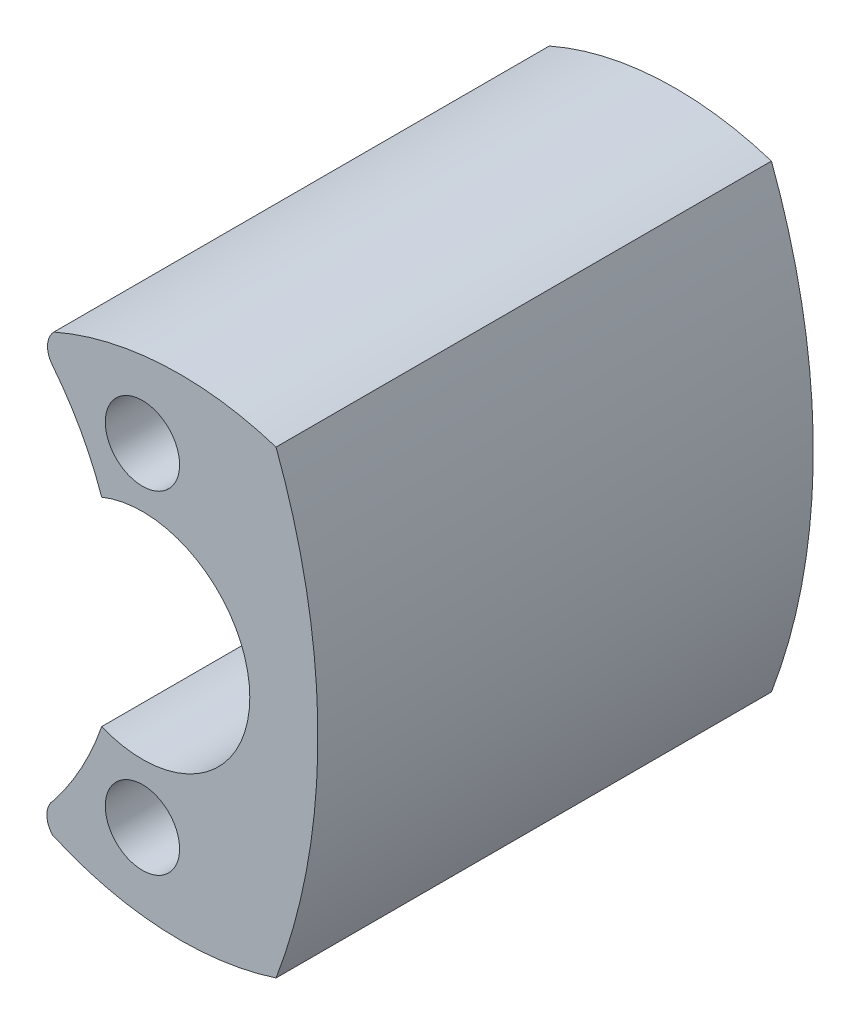
SolidWorks part; units mm, degrees
ref_plane "Front Plane" through (0, 0, 0) normal (0, 0, 1) x (1, 0, 0)
ref_plane "Top Plane" through (0, 0, 0) normal (0, 1, 0) x (1, 0, 0)
ref_plane "Right Plane" through (0, 0, 0) normal (1, 0, 0) x (0, 0, -1)
sketch "Sketch1" plane through (0, 0, 0) normal (0, 0, 1) x (1, 0, 0)
  line L0 (0, 0) -> (0, 9.5) construction
  arc A0 (5.3943, 9.2817) -> (5.3943, -9.2817) centre (-19.2657, 0) cw
  arc A1 (-3.6387, 7.6355) -> (-3.5758, 8.8197) centre (-2.9394, 8.1921) cw
  arc A2 (-3.5758, 8.8197) -> (5.3943, 9.2817) centre (1.5165, -2.7402) cw
  arc A3 (-3.6387, 7.6355) -> (-3.5758, -7.5558) centre (-13.2313, 0) cw
  arc A5 (-3.5758, -7.5558) -> (-3.6256, -8.7977) centre (-2.9797, -8.2016) ccw
  arc A7 (-3.6256, -8.7977) -> (5.3943, -9.2817) centre (1.5165, 2.7402) ccw
  point P12 (0, 0)
  point P13 (5.3943, -9.4493)
  point P18 (5.2209, 9.2817)
extrude "Extrude1" add sketch "Sketch1" along normal blind 20 and the other way blind 0.001
sketch "Sketch3" plane through (0, 0, 20) normal (0, 0, 1) x (1, 0, 0)
  circle A0 centre (0, 6.715) radius 1.5
  circle A1 centre (0, -6.715) radius 1.5
  dimension "D1" = 3
  dimension "D2" = 13.43
extrude "Cut-Extrude1" cut sketch "Sketch3" against normal through all
sketch "Sketch5" plane through (0, 0, -0.001) normal (0, 0, -1) x (-1, 0, 0)
  circle A0 centre (0, 0) radius 4.335
  dimension "D1" = 8.67
extrude "Cut-Extrude2" cut sketch "Sketch5" against normal blind 24
